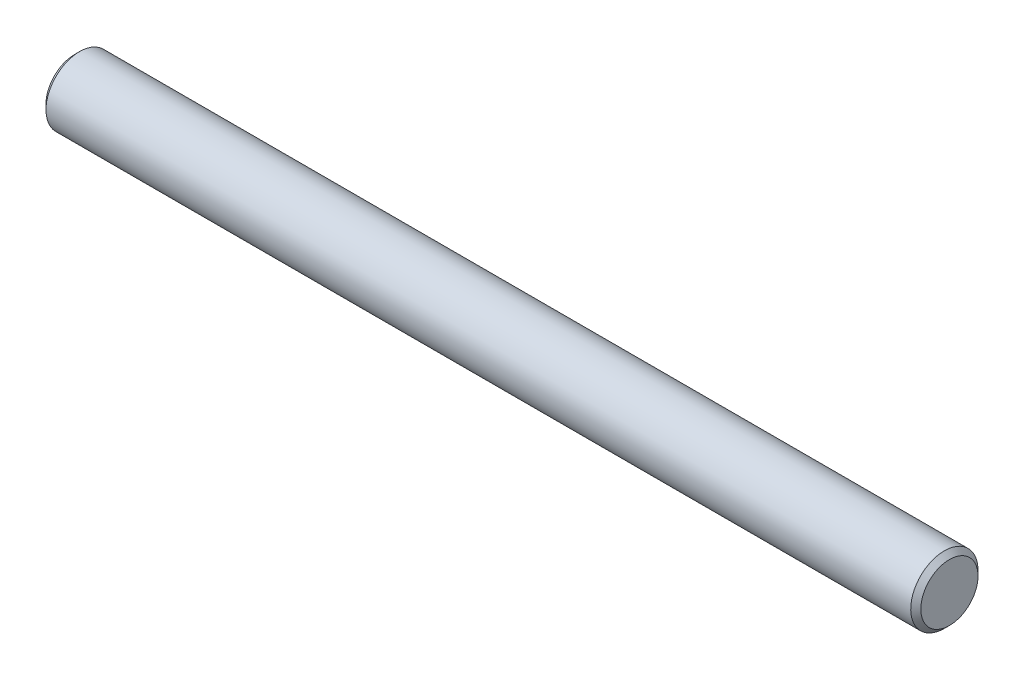
SolidWorks part; units mm, degrees
material "1.0420 (G200)"
ref_plane "Plan de face" through (0, 0, 0) normal (0, 0, 1) x (1, 0, 0)
ref_plane "Plan de dessus" through (0, 0, 0) normal (0, 1, 0) x (1, 0, 0)
ref_plane "Plan de droite" through (0, 0, 0) normal (1, 0, 0) x (0, 0, -1)
sketch "Esquisse1" plane through (0, 0, 0) normal (0, 0, 1) x (1, 0, 0)
  line L0 (0, 0) -> (-52, 0)
  line L1 (-52, 0) -> (-52, 1.7)
  line L2 (-52, 1.7) -> (-51.7, 2)
  line L3 (-51.7, 2) -> (-0.3, 2)
  line L4 (-0.3, 2) -> (0, 1.7)
  line L5 (0, 1.7) -> (0, 0)
  dimension "D1" = 0.3
  dimension "D2" = 0.3
  dimension "D3" = 2
  dimension "D4" = 0.3
  dimension "D5" = 0.3
  dimension "D6" = 52
revolve "Révolution1" add sketch "Esquisse1" angle 360 about L0
